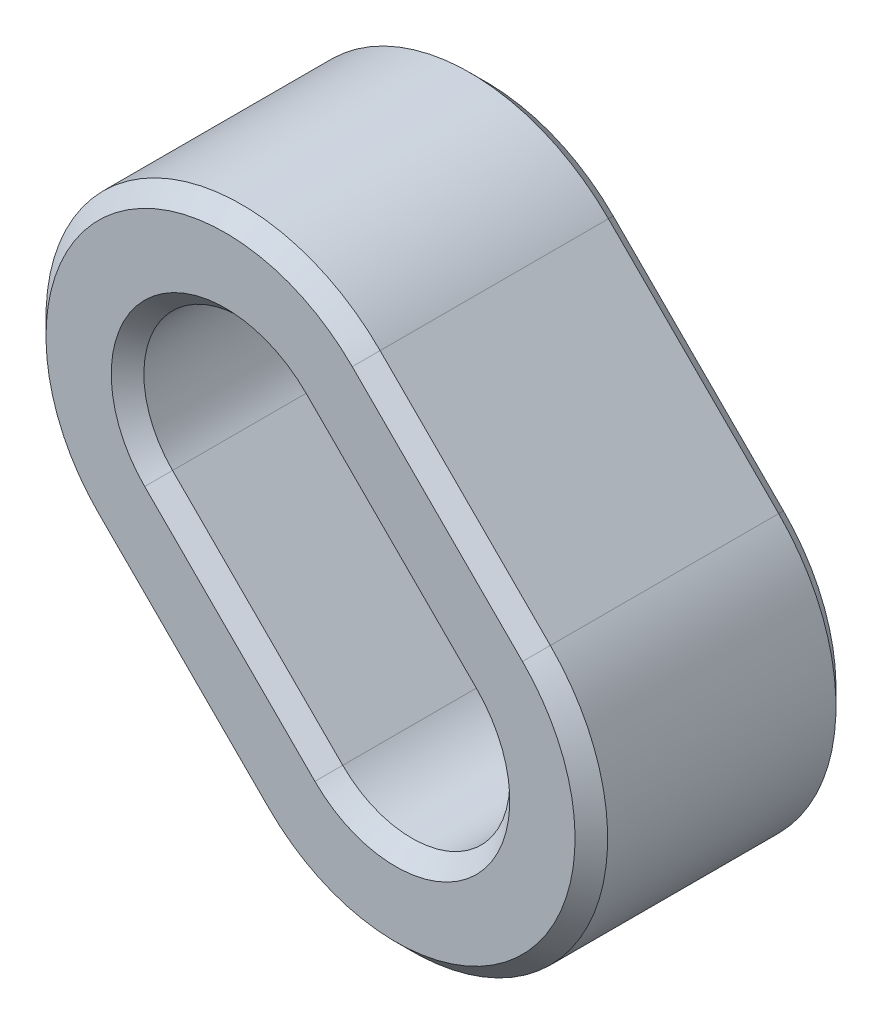
SolidWorks part; units mm, degrees
ref_plane "Front Plane" through (0, 0, 0) normal (0, 0, 1) x (1, 0, 0)
ref_plane "Top Plane" through (0, 0, 0) normal (0, 1, 0) x (1, 0, 0)
ref_plane "Right Plane" through (0, 0, 0) normal (1, 0, 0) x (0, 0, -1)
sketch "Sketch1" plane through (0, 0, 0) normal (0, 0, 1) x (1, 0, 0)
  line L0 (69.9002, 117.5574) -> (75.1187, 112.3389)
  line L1 (78.3855, 126.0426) -> (83.604, 120.8242)
  line L5 (72.0216, 119.6787) -> (77.24, 114.4602)
  line L6 (76.2642, 123.9213) -> (81.4826, 118.7029)
  arc A0 (77.24, 114.4602) -> (81.4826, 118.7029) centre (79.3613, 116.5816) ccw
  arc A1 (75.1187, 112.3389) -> (83.604, 120.8242) centre (79.3613, 116.5816) ccw
  arc A2 (78.3855, 126.0426) -> (69.9002, 117.5574) centre (74.1429, 121.8) ccw
  arc A17 (76.2642, 123.9213) -> (72.0216, 119.6787) centre (74.1429, 121.8) ccw
  dimension "D2" = 6
  dimension "D5" = 6
  dimension "D1" = 3
  dimension "D3" = 7.38
extrude "Boss-Extrude1" add sketch "Sketch1" along normal blind 8
chamfer "Chamfer1" distance 0.5 angle 45 16 edges at (78.8734, 121.3121, 0) (81.4826, 114.4602, 0) (74.6308, 117.0695, 0) (72.0216, 123.9213, 0) (72.5095, 114.9481, 0) (83.604, 112.3389, 0) (80.9947, 123.4334, 0) (69.9002, 126.0426, 0) (81.4826, 114.4602, 8) (78.8734, 121.3121, 8) (72.0216, 123.9213, 8) (74.6308, 117.0695, 8) (80.9947, 123.4334, 8) (83.604, 112.3389, 8) (72.5095, 114.9481, 8) (69.9002, 126.0426, 8)
